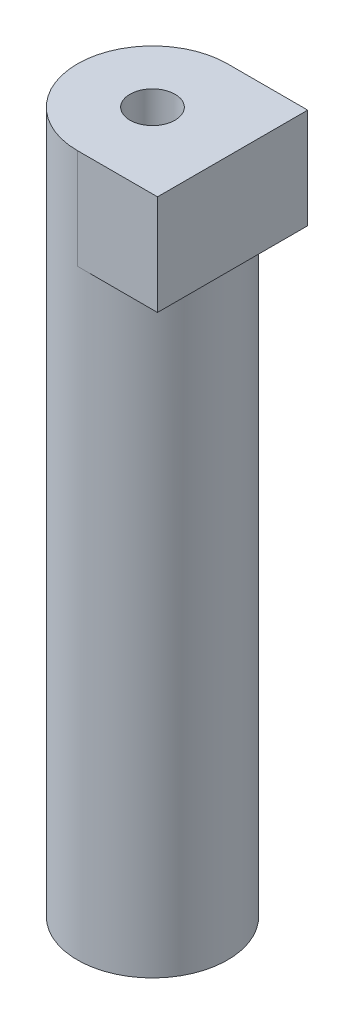
SolidWorks part; units mm, degrees
ref_plane "Front Plane" through (0, 0, 0) normal (0, 0, 1) x (1, 0, 0)
ref_plane "Top Plane" through (0, 0, 0) normal (0, 1, 0) x (1, 0, 0)
ref_plane "Right Plane" through (0, 0, 0) normal (1, 0, 0) x (0, 0, -1)
ref_plane "Plane1"
sketch "Sketch1" plane through (0, 0, 0) normal (0, 1, 0) x (-1, 0, 0)
  circle A0 centre (0, 0) radius 7.5
  dimension "D1" = 15
extrude "Extrusion1" add sketch "Sketch1" along normal blind 160
sketch "Sketch2" plane through (0, 160, 0) normal (0, 1, 0) x (-1, 0, 0)
  circle A0 centre (0, 0) radius 2.25
  dimension "D1" = 4.5
extrude "Extrusion2" cut sketch "Sketch2" against normal blind 80
ref_plane "Plane2"
sketch "Sketch3" plane through (0, 160, 0) normal (0, 1, 0) x (1, 0, 0)
  line L0 (0, -7.5) -> (8, -7.5)
  line L1 (8, -7.5) -> (8, 7.5)
  line L2 (8, 7.5) -> (0, 7.5)
  arc A0 (0, -7.5) -> (0, 7.5) centre (0, 0) ccw
extrude "Extrusion3" add sketch "Sketch3" against normal blind 10
sketch "Sketch4" plane through (0, 0, 0) normal (0, -1, 0) x (1, 0, 0)
  circle A0 centre (0, 0) radius 9.9883
extrude "Extrusion4" cut sketch "Sketch4" against normal blind 45
sketch "Sketch5" plane through (0, 45, 0) normal (0, -1, 0) x (1, 0, 0)
  circle A0 centre (0, 0) radius 7.5
  circle A1 centre (0, 0) radius 4
  circle M1 centre (0, 0) radius 7.5
  dimension "D1" = 15
extrude "Extrusion5" cut sketch "Sketch5" against normal blind 15 contours A1 M1
sketch "Sketch6" plane through (0, 45, 0) normal (0, -1, 0) x (1, 0, 0)
  circle A0 centre (0, 0) radius 13.0014
extrude "Cut-Extrude1" cut sketch "Sketch6" against normal blind 45 contours A0
